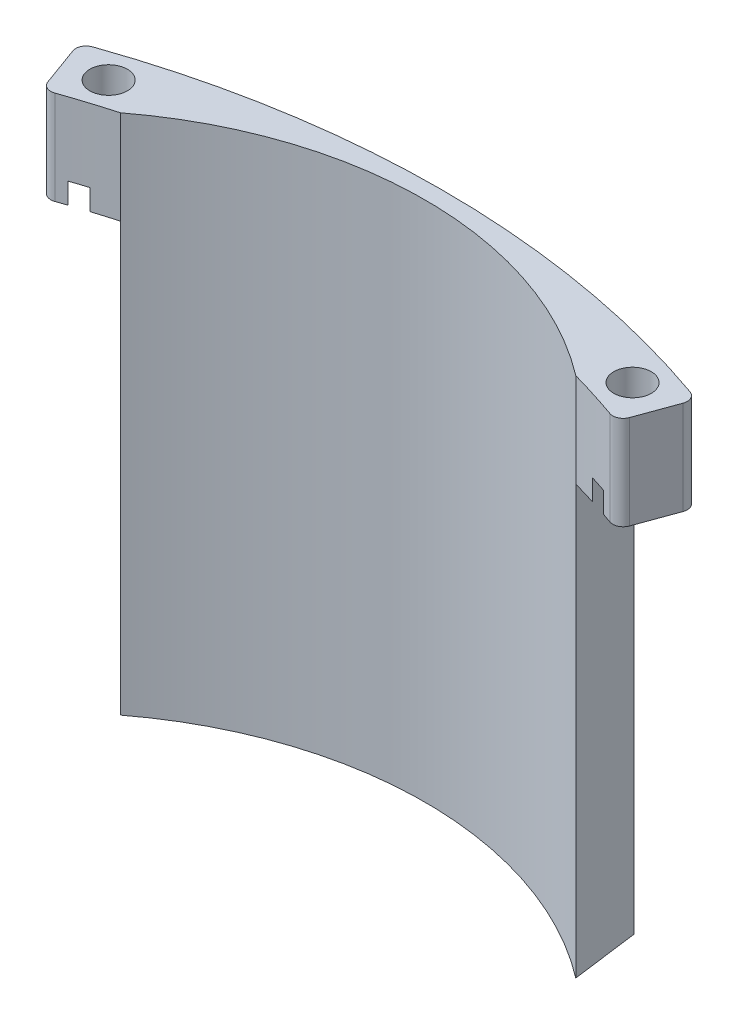
SolidWorks part; units mm, degrees
ref_plane "Front Plane" through (0, 0, 0) normal (0, 0, 1) x (1, 0, 0)
ref_plane "Top Plane" through (0, 0, 0) normal (0, 1, 0) x (1, 0, 0)
ref_plane "Right Plane" through (0, 0, 0) normal (1, 0, 0) x (0, 0, -1)
sketch "Sketch1" plane through (0, 0, 0) normal (0, 1, 0) x (1, 0, 0)
  line L0 (0, 0) -> (-29.5847, 81.2834) construction
  line L1 (29.5847, 81.2834) -> (0, 0) construction
  line L2 (29.5847, 81.2834) -> (27.5326, 75.6453)
  line L3 (-29.5847, 81.2834) -> (-27.5326, 75.6453)
  line L4 (0, -96.25) -> (0, 96.25) construction
  line L5 (-25.1089, 79.6354) -> (0, 0) construction
  line L6 (0, 0) -> (25.1089, 79.6354) construction
  circle A0 centre (0, 0) radius 87.5 construction
  arc A1 (-28.5587, 78.4643) -> (28.5587, 78.4643) centre (0, 0) cw construction
  arc A2 (-29.5847, 81.2834) -> (29.5847, 81.2834) centre (0, 0) cw
  arc A4 (-27.5326, 75.6453) -> (-21.8219, 77.4858) centre (0, 0) cw
  arc A5 (27.5326, 75.6453) -> (21.8219, 77.4858) centre (0, 0) ccw
  arc A6 (-21.8219, 77.4858) -> (21.8219, 77.4858) centre (0, 48.8536) cw
  point P9 (28.5587, 78.4643)
  point P14 (-25.1089, 79.6354)
  point P15 (25.1089, 79.6354)
  dimension "D1" = 175
  dimension "D10" = 36
  dimension "D2" = 1
  dimension "D3" = 6
  dimension "D4" = 40
  dimension "D5" = 20
  dimension "D6" = 35
  dimension "D7" = 17.5
  dimension "D8" = 6
  dimension "D9" = 6
extrude "Boss-Extrude1" add sketch "Sketch1" against normal blind 50
hole_wizard "M3 Clearance Hole1" positions "Sketch2" profile "Sketch3" hole size "M3" standard "DIN" end condition up to next
sketch "Sketch2" plane through (0, 0, 0) normal (0, 1, 0) x (1, 0, 0)
  point P0 (-25.1089, 79.6354)
  point P3 (25.1089, 79.6354)
sketch "Sketch3" plane through (-25.1089, 0, -79.6354) normal (1, 0, 0) x (0, 0, 1)
  line L0 (0, 0) -> (0, 50)
  line L1 (0, 50) -> (1.8, 50)
  line L2 (1.8, 50) -> (1.8, 0)
  line L5 (1.8, 0) -> (0, 0)
  line L11 (0, -6.35) -> (0, 107.95) construction
  dimension "Thru Hole Dia." = 3.6
  dimension "Thru Hole Depth" = 50
sketch "Sketch4" plane through (0, -50, 0) normal (0, -1, 0) x (1, 0, 0)
  line L0 (-27.5326, -75.6453) -> (-29.5847, -81.2834)
  line L1 (27.5326, -75.6453) -> (29.5847, -81.2834)
  line L2 (21.8219, -77.4858) -> (20.9788, -83.9175)
  line L3 (-21.8219, -77.4858) -> (-20.9788, -83.9175)
  arc A0 (-27.5326, -75.6453) -> (-21.8219, -77.4858) centre (0, 0) ccw
  arc A1 (27.5326, -75.6453) -> (21.8219, -77.4858) centre (0, 0) cw
  arc A2 (-29.5847, -81.2834) -> (29.5847, -81.2834) centre (0, 0) ccw construction
  arc A3 (-29.5847, -81.2834) -> (-20.9788, -83.9175) centre (0, 0) ccw
  arc A4 (20.9788, -83.9175) -> (29.5847, -81.2834) centre (0, 0) ccw
  arc A5 (-27.5326, -75.6453) -> (-21.8219, -77.4858) centre (0, 0) ccw construction
  dimension "D1" = 9
extrude "Cut-Extrude1" cut sketch "Sketch4" against normal blind 41
sketch "Sketch5" plane through (0, -9, 0) normal (0, -1, 0) x (-1, 0, 0)
  line L1 (25.5592, 76.2006) -> (28.3086, 78.3079)
  line L2 (28.3086, 78.3079) -> (27.8584, 81.7426)
  line L3 (27.8584, 81.7426) -> (24.6587, 83.0701)
  line L4 (24.6587, 83.0701) -> (21.9093, 80.9628)
  line L5 (21.9093, 80.9628) -> (22.3595, 77.5281)
  line L6 (22.3595, 77.5281) -> (25.5592, 76.2006)
  line L8 (20.9788, 83.9175) -> (21.8219, 77.4858) construction
  line L9 (-21.8219, 77.4858) -> (-20.9788, 83.9175) construction
  line L10 (-28.3086, 78.3079) -> (-25.5592, 76.2006)
  line L11 (-25.5592, 76.2006) -> (-22.3595, 77.5281)
  line L12 (-22.3595, 77.5281) -> (-21.9093, 80.9628)
  line L13 (-21.9093, 80.9628) -> (-24.6587, 83.0701)
  line L14 (-24.6587, 83.0701) -> (-27.8584, 81.7426)
  line L15 (-27.8584, 81.7426) -> (-28.3086, 78.3079)
  circle A0 centre (25.1089, 79.6354) radius 3 construction
  circle A1 centre (-25.1089, 79.6354) radius 3 construction
  dimension "D1" = 6
  dimension "D2" = 6
extrude "Cut-Extrude2" cut sketch "Sketch5" against normal blind 2
fillet "Fillet1" radius 1 4 edges at (29.5847, -4.5, -81.2834) (27.5326, -4.5, -75.6453) (-29.5847, -4.5, -81.2834) (-27.5326, -4.5, -75.6453)
equation "\"D5@Sketch1\"=\"D4@Sketch1\"/2"
equation "\"D7@Sketch1\"=\"D6@Sketch1\"/2"
equation "\"D8@Sketch1\"=\"D9@Sketch1\""
